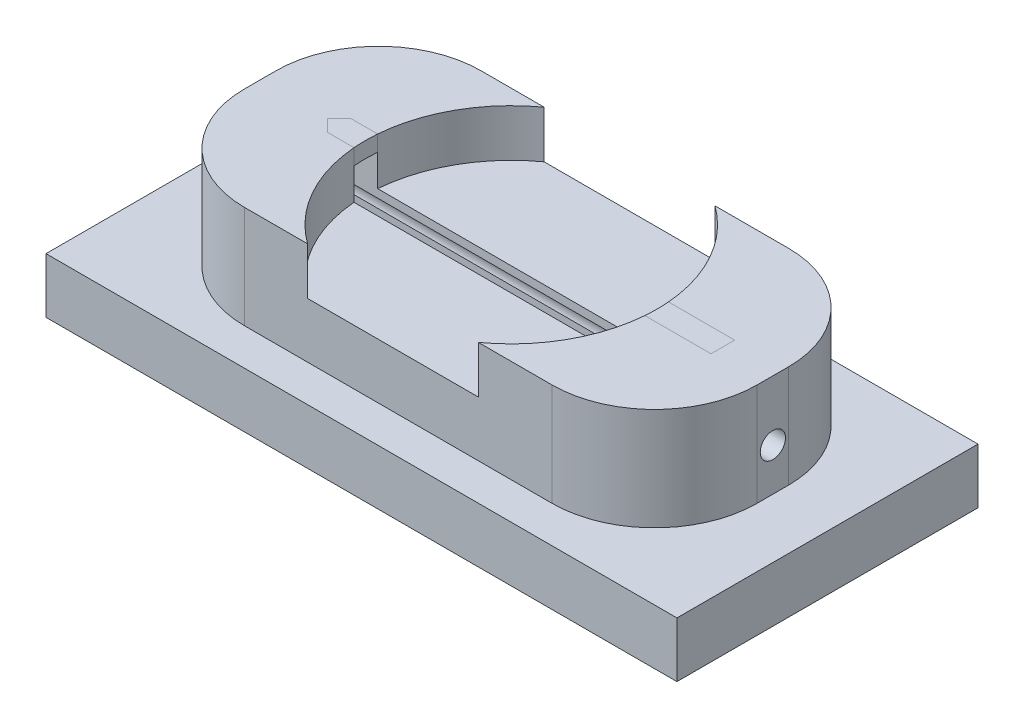
SolidWorks part; units mm, degrees
ref_plane "Front Plane" through (0, 0, 0) normal (0, 0, 1) x (1, 0, 0)
ref_plane "Top Plane" through (0, 0, 0) normal (0, 1, 0) x (1, 0, 0)
ref_plane "Right Plane" through (0, 0, 0) normal (1, 0, 0) x (0, 0, -1)
sketch "Sketch1" plane through (0, 0, 0) normal (0, 1, 0) x (1, 0, 0)
  line L1 (-25, -15) -> (40, -15)
  line L2 (-25, -15) -> (-25, 15)
  line L3 (-25, 15) -> (40, 15)
  line L4 (40, -15) -> (40, 15)
  line L5 (-25, -15) -> (40, 15) construction
  line L6 (-25, 15) -> (40, -15) construction
  point P0 (0, 0)
  dimension "D1" = 30
  dimension "D2" = 65
extrude "Boss-Extrude1" add sketch "Sketch1" along normal blind 58
sketch "Sketch2" plane through (0, 58, 0) normal (0, 1, 0) x (1, 0, 0)
  line L0 (-15, 1.5) -> (15, 1.5)
  line L3 (15, -1.5) -> (-15, -1.5)
  line L4 (-15, -1.5) -> (-16.5, 0)
  line L5 (-16.5, 0) -> (-15, 1.5)
  line L6 (15, 1.5) -> (33.657, 1.5)
  line L7 (33.657, 1.5) -> (33.657, -1.5)
  line L8 (33.657, -1.5) -> (15, -1.5)
  point P2 (-15, 5)
  dimension "D1" = 15
  dimension "D2" = 15
  dimension "D3" = 15
  dimension "D4" = 15
  dimension "D5" = 1.5
  dimension "D6" = 1.5
extrude "Cut-Extrude1" cut sketch "Sketch2" against normal blind 70
sketch "Sketch3" plane through (-25, 0, 0) normal (-1, 0, 0) x (0, 0, 1)
  line L0 (-15, 58) -> (15, 58) construction
  circle A0 centre (0, 50.4) radius 1.6
  point P2 (0, 49.3874)
  dimension "D1" = 3.2
  dimension "D2" = 7.6
extrude "Cut-Extrude2" cut sketch "Sketch3" against normal through all and the other way through all
fillet "Fillet1" radius 13 4 edges at (40, 29, -15) (-25, 29, -15) (40, 29, 15) (-25, 29, 15)
ref_plane "Plane2" through (0, -10, 0) normal (0, -1, 0) x (-1, 0, 0)
sketch "Sketch15" plane through (0, -10, 0) normal (0, -1, 0) x (-1, 0, 0)
  line L1 (-41.9055, 15.8797) -> (41.7906, 15.8797)
  line L2 (-41.9055, 15.8797) -> (-41.9055, -15.8187)
  line L3 (-41.9055, -15.8187) -> (41.7906, -15.8187)
  line L4 (41.7906, 15.8797) -> (41.7906, -15.8187)
extrude "Cut-Extrude7" cut sketch "Sketch15" against normal blind 50
ref_plane "Plane3" through (0, 40, 0) normal (0, -1, 0) x (-1, 0, 0)
sketch "Sketch16" plane through (0, 40, 0) normal (0, -1, 0) x (-1, 0, 0)
  line L0 (-40, 2) -> (-40, -2) construction
  line L1 (-47.5, 18.511) -> (32.5, 18.511)
  line L2 (-47.5, 18.511) -> (-47.5, -19.6628)
  line L3 (-47.5, -19.6628) -> (32.5, -19.6628)
  line L4 (32.5, 18.511) -> (32.5, -19.6628)
  line L5 (25, -2) -> (25, 2) construction
  dimension "D1" = 80
  dimension "D2" = 7.5
  dimension "D3" = 7.5
extrude "Boss-Extrude4" add sketch "Sketch16" along normal blind 2 and the other way blind 5
ref_plane "Plane4" through (0, 58, 0) normal (0, 1, 0) x (1, 0, 0)
sketch "Sketch18" plane through (0, 58, 0) normal (0, 1, 0) x (1, 0, 0)
  circle A0 centre (6.8285, 0) radius 18.5
  dimension "D1" = 37
sketch "Sketch19" plane through (0, 58, 0) normal (0, 1, 0) x (1, 0, 0)
  line L0 (33.657, 1.5) -> (-15, 1.5) construction
  line L1 (-15, -1.5) -> (33.657, -1.5) construction
  line L2 (-11.6106, 1.5) -> (-15, 1.5)
  line L3 (-15, 1.5) -> (-16.5, 0)
  line L4 (-16.5, 0) -> (-15, -1.5)
  line L5 (-15, -1.5) -> (-11.6106, -1.5)
  line L6 (-15, -1.5) -> (33.657, -1.5) construction
  line L7 (25.2676, 1.5) -> (33.657, 1.5)
  line L8 (33.657, 1.5) -> (33.657, -1.5)
  line L9 (33.657, -1.5) -> (25.2676, -1.5)
  arc A0 (-11.6106, 1.5) -> (-11.6106, -1.5) centre (6.8285, 0) ccw
  circle A1 centre (6.8285, 0) radius 18.5 construction
  arc A2 (25.2676, 1.5) -> (25.2676, -1.5) centre (6.8285, 0) cw
extrude "Cut-Extrude8" cut sketch "Sketch18" against normal blind 6 contours A0
extrude "Boss-Extrude5" add sketch "Sketch19" against normal blind 2 separate body
